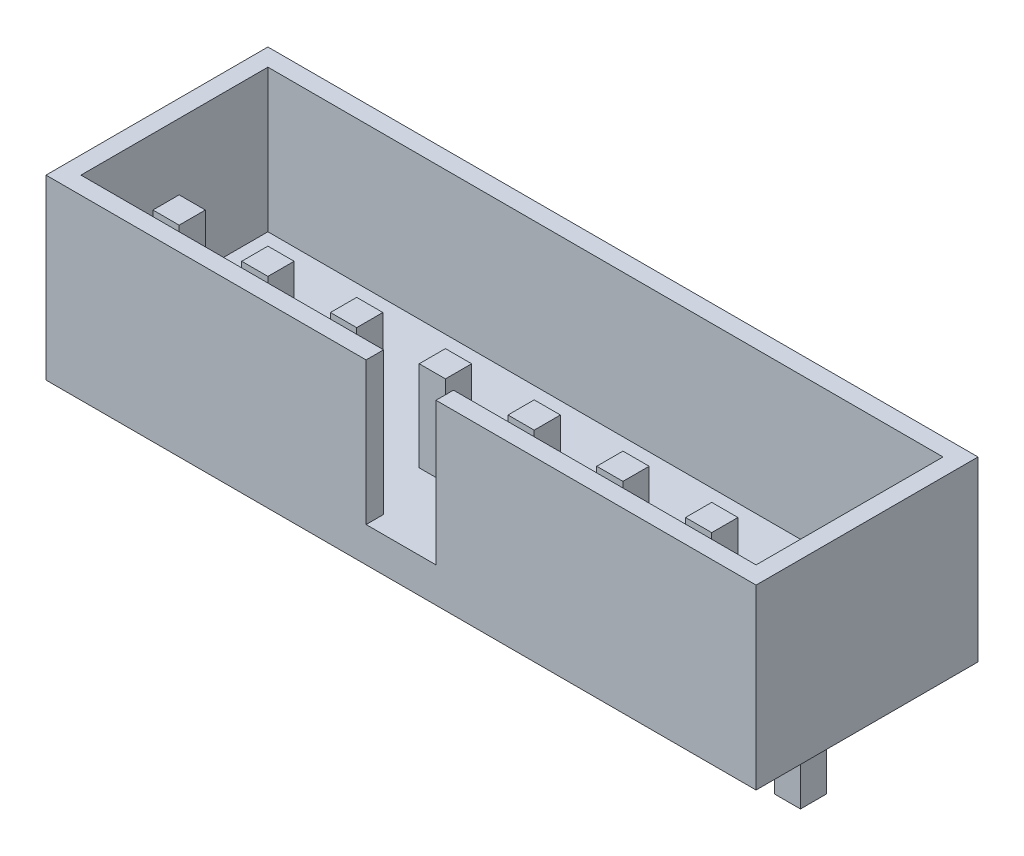
SolidWorks part; units mm, degrees
ref_plane "前视基准面" through (0, 0, 0) normal (0, 0, 1) x (1, 0, 0)
ref_plane "上视基准面" through (0, 0, 0) normal (0, 1, 0) x (1, 0, 0)
ref_plane "右视基准面" through (0, 0, 0) normal (1, 0, 0) x (0, 0, -1)
sketch "草图1" plane through (0, 0, 0) normal (0, 1, 0) x (1, 0, 0)
  line L0 (0, 7.1914) -> (0, -5.4429) construction
  line L1 (-10.16, 3.175) -> (10.16, 3.175)
  line L2 (-10.16, 3.175) -> (-10.16, -3.175)
  line L3 (-10.16, -3.175) -> (10.16, -3.175)
  line L4 (10.16, 3.175) -> (10.16, -3.175)
  line L5 (-10.6234, 0) -> (16.1963, 0) construction
  dimension "D1" = 20.32
  dimension "D2" = 6.35
extrude "拉伸1" add sketch "草图1" along normal blind 5.08
sketch "草图2" plane through (0, 5.08, 0) normal (0, 1, 0) x (-1, 0, 0)
  line L8 (9.66, -2.675) -> (9.66, 2.675)
  line L9 (9.66, 2.675) -> (-9.66, 2.675)
  line L10 (-9.66, 2.675) -> (-9.66, -2.675)
  line L11 (-9.66, -2.675) -> (9.66, -2.675)
  line L12 (9.66, -2.675) -> (9.66, 2.675)
  line L13 (9.66, 2.675) -> (-9.66, 2.675)
  line L14 (-9.66, 2.675) -> (-9.66, -2.675)
  line L15 (-9.66, -2.675) -> (9.66, -2.675)
  dimension "D1" = 0.5
extrude "切除-拉伸1" cut sketch "草图2" against normal offset from surface (4.08 mm away) 1 up to face at (0, 0, 0)
sketch "草图3" plane through (0, 0, 3.175) normal (0, 0, 1) x (1, 0, 0)
  line L0 (-10.16, 5.08) -> (10.16, 5.08) construction
  line L1 (-1, 5.08) -> (1, 5.08)
  line L2 (-1, 5.08) -> (-1, 1)
  line L3 (-1, 1) -> (1, 1)
  line L4 (1, 5.08) -> (1, 1)
  line L5 (9.66, 1) -> (-9.66, 1) construction
  line L6 (0, -1.5083) -> (0, 12.2426) construction
  dimension "D1" = 2
extrude "切除-拉伸2" cut sketch "草图3" against normal blind 1
sketch "草图4" plane through (0, 0, 0) normal (0, -1, 0) x (1, 0, 0)
  line L0 (7.6775, 0.635) -> (-8.5467, 0.635) construction
  line L1 (-10.16, 3.175) -> (10.16, 3.175) construction
  line L2 (0, -3.6953) -> (0, 4.0669) construction
  line L3 (-1.27, 2.1009) -> (-1.27, -0.7012) construction
  line L4 (-1.645, 1.01) -> (-0.895, 1.01)
  line L5 (-1.645, 1.01) -> (-1.645, 0.26)
  line L6 (-1.645, 0.26) -> (-0.895, 0.26)
  line L7 (-0.895, 1.01) -> (-0.895, 0.26)
  line L8 (0.895, 1.01) -> (1.645, 1.01)
  line L9 (0.895, 1.01) -> (0.895, 0.26)
  line L10 (0.895, 0.26) -> (1.645, 0.26)
  line L11 (1.645, 1.01) -> (1.645, 0.26)
  line L12 (2.54, -3.6953) -> (2.54, 4.0669) construction
  line L13 (3.435, 1.01) -> (4.185, 1.01)
  line L14 (3.435, 1.01) -> (3.435, 0.26)
  line L15 (3.435, 0.26) -> (4.185, 0.26)
  line L16 (4.185, 1.01) -> (4.185, 0.26)
  line L17 (5.08, -3.6953) -> (5.08, 4.0669) construction
  line L18 (5.975, 1.01) -> (6.725, 1.01)
  line L19 (5.975, 1.01) -> (5.975, 0.26)
  line L20 (5.975, 0.26) -> (6.725, 0.26)
  line L21 (6.725, 1.01) -> (6.725, 0.26)
  line L22 (7.62, -3.6953) -> (7.62, 4.0669) construction
  line L23 (-4.185, 1.01) -> (-3.435, 1.01)
  line L24 (-4.185, 1.01) -> (-4.185, 0.26)
  line L25 (-4.185, 0.26) -> (-3.435, 0.26)
  line L26 (-3.435, 1.01) -> (-3.435, 0.26)
  line L27 (-3.81, 2.1009) -> (-3.81, -0.7012) construction
  line L28 (5.1375, 0.635) -> (-11.0867, 0.635) construction
  line L29 (-6.725, 1.01) -> (-5.975, 1.01)
  line L30 (-6.725, 1.01) -> (-6.725, 0.26)
  line L31 (-6.725, 0.26) -> (-5.975, 0.26)
  line L32 (-5.975, 1.01) -> (-5.975, 0.26)
  line L33 (-6.35, 2.1009) -> (-6.35, -0.7012) construction
  line L34 (2.5975, 0.635) -> (-13.6267, 0.635) construction
  line L35 (-9.265, 1.01) -> (-8.515, 1.01)
  line L36 (-9.265, 1.01) -> (-9.265, 0.26)
  line L37 (-9.265, 0.26) -> (-8.515, 0.26)
  line L38 (-8.515, 1.01) -> (-8.515, 0.26)
  line L39 (-8.89, 2.1009) -> (-8.89, -0.7012) construction
  line L40 (0.0575, 0.635) -> (-16.1667, 0.635) construction
  line L41 (8.515, 1.01) -> (9.265, 1.01)
  line L42 (8.515, 1.01) -> (8.515, 0.26)
  line L43 (8.515, 0.26) -> (9.265, 0.26)
  line L44 (9.265, 1.01) -> (9.265, 0.26)
  line L45 (10.16, -3.6953) -> (10.16, 4.0669) construction
  dimension "D1" = 2.54
  dimension "D2" = 0.75
  dimension "D3" = 0.75
  dimension "D4" = 1.27
  dimension "D5" = 5
  dimension "D6" = 4
extrude "拉伸2" add sketch "草图4" along normal blind 2 and the other way offset from surface (3.58 mm away) 1.5 other way up to face at (0, 5.08, 0.975)
